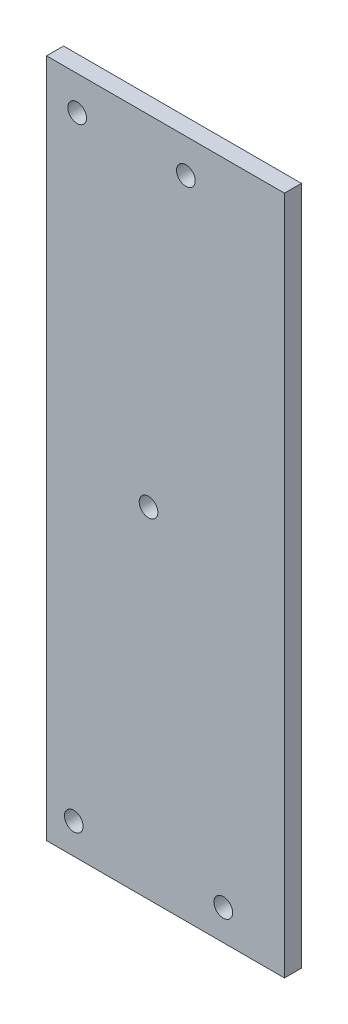
SolidWorks part; units mm, degrees
ref_plane "정면" through (0, 0, 0) normal (0, 0, 1) x (1, 0, 0)
ref_plane "윗면" through (0, 0, 0) normal (0, 1, 0) x (1, 0, 0)
ref_plane "우측면" through (0, 0, 0) normal (1, 0, 0) x (0, 0, -1)
sketch "스케치1" plane through (0, 0, 0) normal (0, 0, 1) x (1, 0, 0)
  line L1 (-50, 100) -> (50, 100)
  line L2 (-50, 100) -> (-50, -100)
  line L3 (-50, -100) -> (50, -100)
  line L4 (50, 100) -> (50, -100)
  line L5 (-50, 100) -> (50, -100) construction
  line L6 (-50, -100) -> (50, 100) construction
  point P0 (0, 0)
  dimension "D1" = 100
  dimension "D2" = 200
extrude "보스-돌출1" add sketch "스케치1" along normal blind 5
sketch "스케치3" plane through (0, 0, 0) normal (0, 0, -1) x (-1, 0, 0)
  text T0 "front"
extrude "컷-돌출2" cut sketch "스케치3" against normal blind 0.001
ref_plane "평면1" through (0, 0, -5) normal (0, 0, -1) x (-1, 0, 0)
sketch "스케치13" plane through (0, 0, 5) normal (0, 0, 1) x (1, 0, 0)
  line L0 (-50, -100) -> (50, -100) construction
  line L1 (50, 100) -> (40, 100)
  line L2 (50, 100) -> (50, -100)
  line L3 (50, -100) -> (40, -100)
  line L4 (40, 100) -> (40, -100)
  line L5 (0, -2.75) -> (0, 2.75) construction
  line L6 (-40, 100) -> (-40, -100)
  line L7 (-50, -100) -> (-40, -100)
  line L8 (-50, 100) -> (-50, -100)
  line L9 (-50, 100) -> (-40, 100)
  dimension "D1" = 10
extrude "컷-돌출4" cut sketch "스케치13" against normal blind 10
sketch "스케치14" plane through (0, 0, 5) normal (0, 0, 1) x (1, 0, 0)
  line L0 (-40, -100) -> (40, -100) construction
  line L1 (40, 100) -> (30, 100)
  line L2 (40, 100) -> (40, -100)
  line L3 (40, -100) -> (30, -100)
  line L4 (30, 100) -> (30, -100)
  dimension "D1" = 10
extrude "컷-돌출5" cut sketch "스케치14" against normal blind 10
sketch "스케치15" plane through (0, 0, 0) normal (0, 0, -1) x (-1, 0, 0)
  line L0 (-30, 100) -> (-30, -100) construction
  line L1 (-30, 100) -> (40, 100) construction
  line L2 (40, -100) -> (40, 100) construction
  circle A0 centre (-1, 90) radius 2.75
  circle A1 centre (31, 90) radius 2.75
  dimension "D2" = 5.5
  dimension "D3" = 5.5
  dimension "D1" = 9
  dimension "D4" = 29
  dimension "D5" = 10
  dimension "D6" = 10
extrude "컷-돌출6" cut sketch "스케치15" against normal through all
sketch "스케치17" plane through (0, 0, 0) normal (0, 0, -1) x (-1, 0, 0)
  line L0 (40, -100) -> (-30, -100) construction
  line L2 (-30, 100) -> (-30, -100) construction
  circle A1 centre (10, 0) radius 2.75
  dimension "D4" = 5.5
  dimension "D5" = 40
  dimension "D6" = 100
extrude "컷-돌출8" cut sketch "스케치17" against normal blind 10
sketch "스케치18" plane through (0, 0, 0) normal (0, 0, -1) x (-1, 0, 0)
  line L0 (-30, 100) -> (-30, -100) construction
  line L1 (40, -100) -> (40, 100) construction
  line L3 (40, -100) -> (-30, -100) construction
  circle A0 centre (32, -91) radius 2.75
  circle A1 centre (-12, -91) radius 2.75
  dimension "D1" = 5.5
  dimension "D2" = 5.5
  dimension "D3" = 18
  dimension "D4" = 8
  dimension "D5" = 9
  dimension "D6" = 9
extrude "컷-돌출9" cut sketch "스케치18" against normal blind 10
